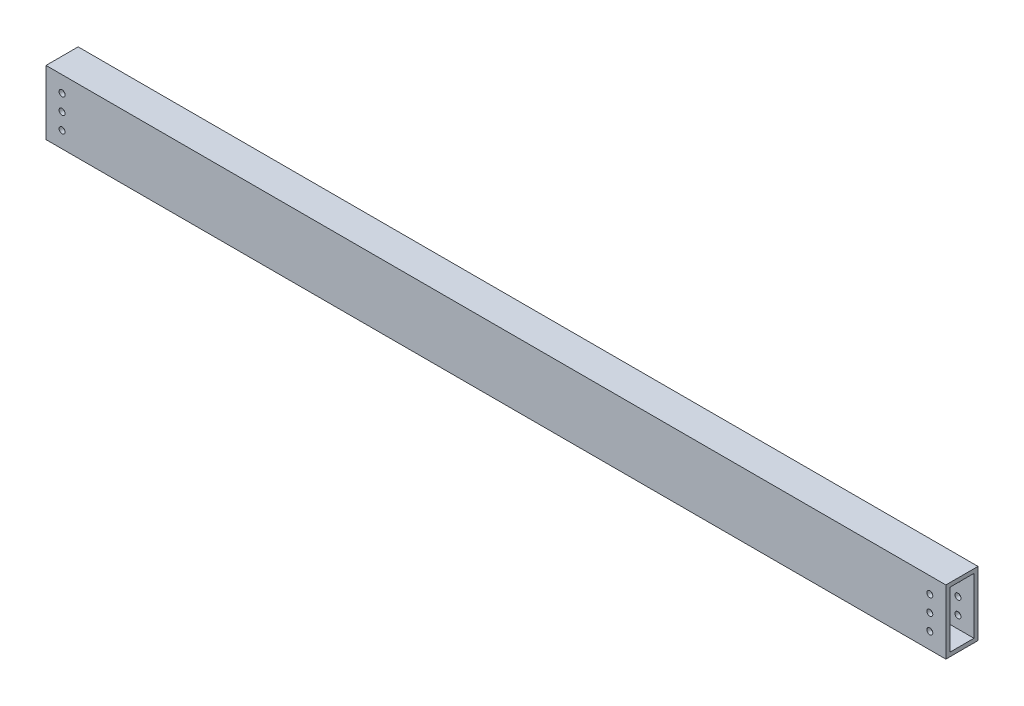
SolidWorks part; units mm, degrees
ref_plane "Front Plane" through (0, 0, 0) normal (0, 0, 1) x (1, 0, 0)
ref_plane "Top Plane" through (0, 0, 0) normal (0, 1, 0) x (1, 0, 0)
ref_plane "Right Plane" through (0, 0, 0) normal (1, 0, 0) x (0, 0, -1)
sketch "Sketch1" plane through (0, 0, 0) normal (1, 0, 0) x (0, 0, -1)
  line L1 (-12.7, 25.4) -> (12.7, 25.4)
  line L2 (-12.7, 25.4) -> (-12.7, -25.4)
  line L3 (-12.7, -25.4) -> (12.7, -25.4)
  line L4 (12.7, 25.4) -> (12.7, -25.4)
  line L5 (0, -25.4) -> (0, 25.4) construction
  line L6 (-12.7, 0) -> (12.7, 0) construction
  point P0 (0, 0)
  dimension "D1" = 25.4
  dimension "D2" = 50.8
extrude "Boss-Extrude1" add sketch "Sketch1" along normal mid plane 711.2
shell "Shell1" thickness 3.175
sketch "Sketch2" plane through (0, 0, 12.7) normal (0, 0, 1) x (1, 0, 0)
  line L0 (-342.9, -12.7) -> (-342.9, 12.7) construction
  line L1 (-355.6, 25.4) -> (-355.6, -25.4) construction
  line L2 (0, 0) -> (0, -50000) construction
  line L3 (342.9, -12.7) -> (342.9, 12.7) construction
  circle A0 centre (-342.9, 12.7) radius 2.3813
  circle A1 centre (-342.9, 0) radius 2.3813
  circle A2 centre (-342.9, -12.7) radius 2.3813
  circle A3 centre (342.9, -12.7) radius 2.3813
  circle A4 centre (342.9, 0) radius 2.3813
  circle A5 centre (342.9, 12.7) radius 2.3813
  point P9 (-342.9, 0)
  point P19 (342.9, 0)
  dimension "D1" = 4.7625
  dimension "D2" = 12.7
  dimension "D3" = 12.7
extrude "Cut-Extrude1" cut sketch "Sketch2" against normal through all
